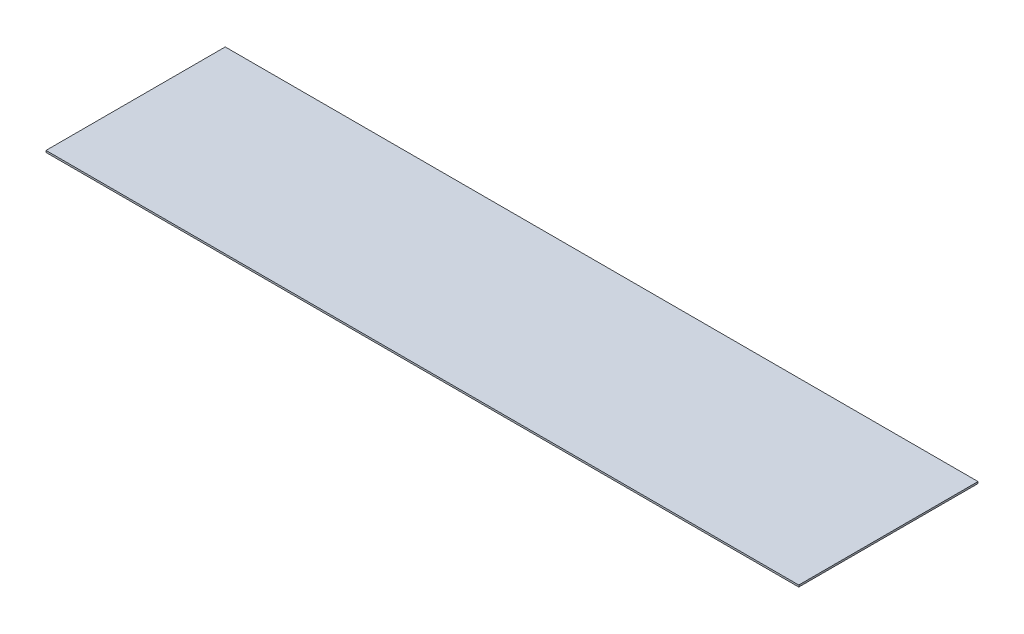
SolidWorks part; units mm, degrees
ref_plane "Front Plane" through (0, 0, 0) normal (0, 0, 1) x (1, 0, 0)
ref_plane "Top Plane" through (0, 0, 0) normal (0, 1, 0) x (1, 0, 0)
ref_plane "Right Plane" through (0, 0, 0) normal (1, 0, 0) x (0, 0, -1)
sketch "Sketch1" plane through (0, 0, 0) normal (0, 1, 0) x (1, 0, 0)
  line L1 (-105, -25) -> (105, -25)
  line L2 (-105, -25) -> (-105, 25)
  line L3 (-105, 25) -> (105, 25)
  line L4 (105, -25) -> (105, 25)
  line L5 (-105, -25) -> (105, 25) construction
  line L6 (-105, 25) -> (105, -25) construction
  point P0 (0, 0)
  dimension "D1" = 210
  dimension "50mm" = 50
extrude "Boss-Extrude1" add sketch "Sketch1" along normal blind 0.5
sketch "Sketch2" plane through (0, 0.5, 0) normal (0, 1, 0) x (1, 0, 0)
  line L0 (0, 25) -> (0, -25) construction
  line L1 (105, 25) -> (-105, 25) construction
  line L2 (-105, -25) -> (105, -25) construction
  line L3 (-52.5, 25) -> (-52.5, -25) construction
  line L4 (52.5, 25) -> (52.5, -25) construction
  dimension "D1" = 52.5
  dimension "D2" = 52.5
other "Flex1" [suppressed] parameters "D0"=200.056, "D1"=52.6405, "D2"=52.6106
